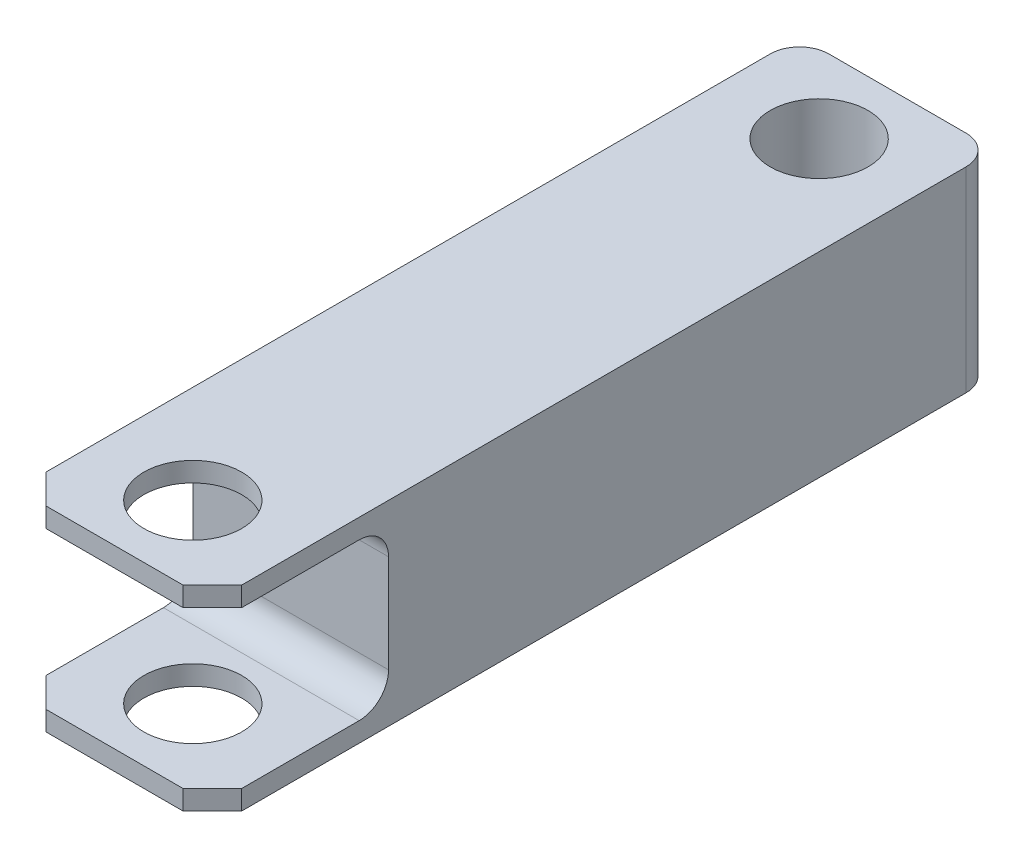
SolidWorks part; units mm, degrees
ref_plane "Front Plane" through (0, 0, 0) normal (0, 0, 1) x (1, 0, 0)
ref_plane "Top Plane" through (0, 0, 0) normal (0, 1, 0) x (1, 0, 0)
ref_plane "Right Plane" through (0, 0, 0) normal (1, 0, 0) x (0, 0, -1)
sketch "Sketch1" plane through (0, 0, 0) normal (0, 0, 1) x (1, 0, 0)
  line L1 (-10, -10) -> (10, -10)
  line L2 (-10, -10) -> (-10, 10)
  line L3 (-10, 10) -> (10, 10)
  line L4 (10, -10) -> (10, 10)
  line L5 (-10, -10) -> (10, 10) construction
  line L6 (-10, 10) -> (10, -10) construction
  point P0 (0, 0)
  dimension "D1" = 20
  dimension "D2" = 20
extrude "Boss-Extrude1" add sketch "Sketch1" along normal blind 80
sketch "Sketch2" plane through (0, 10, 0) normal (0, 1, 0) x (1, 0, 0)
  line L0 (0, 0) -> (0, -8) construction
  line L1 (10, 0) -> (-10, 0) construction
  circle A0 centre (0, -8) radius 5
  dimension "D1" = 10
  dimension "D2" = 8
extrude "Cut-Extrude1" cut sketch "Sketch2" against normal blind 80
sketch "Sketch3" plane through (0, 0, 80) normal (0, 0, 1) x (1, 0, 0)
  line L0 (-10, 10) -> (-10, -10) construction
  line L1 (10, -8) -> (-10, -8)
  line L2 (10, -8) -> (10, 8)
  line L3 (10, 8) -> (-10, 8)
  line L4 (-10, -8) -> (-10, 8)
  line L5 (10, -8) -> (-10, 8) construction
  line L6 (10, 8) -> (-10, -8) construction
  point P0 (0, 0)
  dimension "D1" = 16
extrude "Cut-Extrude2" cut sketch "Sketch3" against normal blind 18
sketch "Sketch4" plane through (0, -10, 0) normal (0, -1, 0) x (1, 0, 0)
  line L0 (0, 0) -> (0, 80) construction
  line L1 (-10, 80) -> (10, 80) construction
  circle A0 centre (0, 72) radius 5
  dimension "D1" = 10
  dimension "D2" = 8
extrude "Cut-Extrude3" cut sketch "Sketch4" against normal blind 92
fillet "Fillet1" radius 3 4 edges at (-10, 0, 0) (10, 0, 0) (0, -8, 62) (0, 8, 62)
chamfer "Chamfer1" distance 3 angle 45 4 edges at (10, 9, 80) (-10, 9, 80) (10, -9, 80) (-10, -9, 80)
